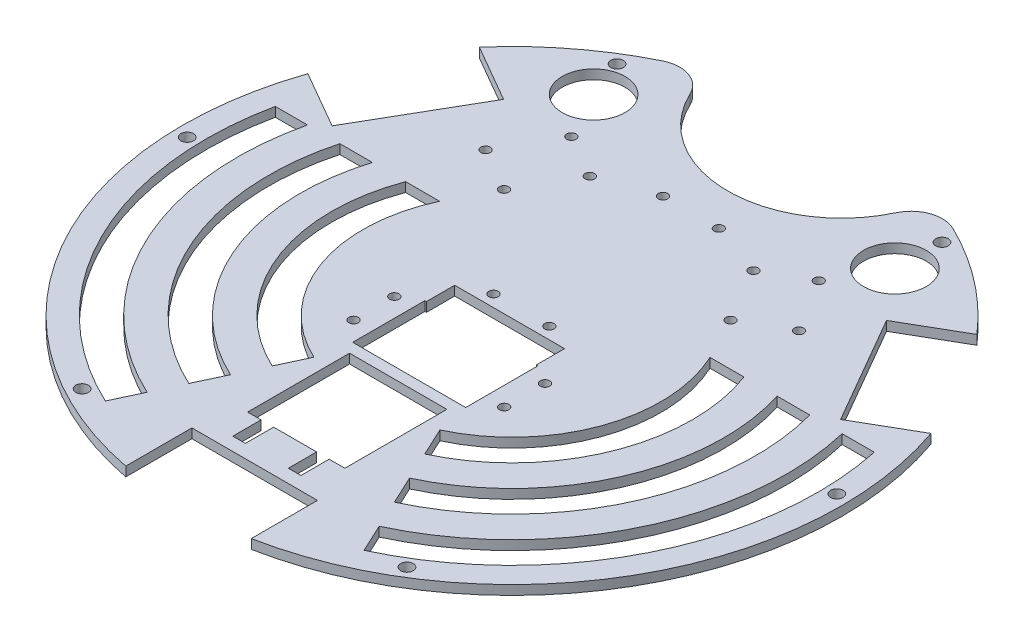
SolidWorks part; units mm, degrees
ref_plane "Alzado" through (0, 0, 0) normal (0, 0, 1) x (1, 0, 0)
ref_plane "Planta" through (0, 0, 0) normal (0, 1, 0) x (1, 0, 0)
ref_plane "Vista lateral" through (0, 0, 0) normal (1, 0, 0) x (0, 0, -1)
sketch "Croquis1" plane through (0, 0, 0) normal (0, 1, 0) x (1, 0, 0)
  circle A0 centre (0, 0) radius 105
  dimension "D1" = 210
extrude "Saliente-Extruir1" add sketch "Croquis1" along normal blind 3
sketch "Croquis2" plane through (0, 3, 0) normal (0, 1, 0) x (1, 0, 0)
  line L0 (-35.7167, 98.7386) -> (35.7167, 98.7386) construction
  line L1 (-29.7198, 68.7386) -> (25.5389, 68.7386) construction
  arc A0 (35.7167, 98.7386) -> (-35.7167, 98.7386) centre (0, 105) cw
  circle A2 centre (0, 0) radius 105 construction
  arc A3 (-35.7167, 98.7386) -> (35.7167, 98.7386) centre (0, 0) cw
  dimension "D1" = 30
extrude "Cortar-Extruir1" cut sketch "Croquis2" against normal up to surface (3 mm away) up to face at (0, 0, 105)
fillet "Redondeo1" radius 10 2 edges at (35.7167, 1.5, -98.7386) (-35.7167, 1.5, -98.7386)
sketch "Croquis3" plane through (0, 3, 0) normal (0, 1, 0) x (1, 0, 0)
  line L0 (0, 0) -> (0, -105) construction
  line L1 (-20, -105) -> (-20, -82) construction
  line L2 (-20, -82) -> (20, -82) construction
  line L3 (20, -82) -> (20, -105) construction
  line L4 (20, -105) -> (-20, -105) construction
  line L5 (-61.0141, 58.3205) -> (-85.2628, 72.3205)
  line L6 (-20, -82) -> (20, -82)
  line L7 (-20, -82) -> (-20, -110)
  line L8 (-20, -110) -> (20, -110)
  line L9 (20, -82) -> (20, -110)
  line L10 (-61.0141, 58.3205) -> (-81.0141, 23.6795)
  line L11 (-81.0141, 23.6795) -> (-105.2628, 37.6795)
  line L12 (-85.2628, 72.3205) -> (-105.2628, 37.6795)
  line L13 (81.0141, 23.6795) -> (105.2628, 37.6795)
  line L14 (81.0141, 23.6795) -> (61.0141, 58.3205)
  line L15 (61.0141, 58.3205) -> (85.2628, 72.3205)
  line L16 (105.2628, 37.6795) -> (85.2628, 72.3205)
  arc A0 (-46.2555, 94.2626) -> (46.2555, 94.2626) centre (0, 0) ccw construction
  point P23 (0, 0)
  point P29 (0, 0)
  point P44 (0, 0)
  dimension "D5" = 3
  dimension "D7" = 110
  dimension "D1" = 20
  dimension "D2" = 40
  dimension "D3" = 23
  dimension "D4" = 105
extrude "Cortar-Extruir12" cut sketch "Croquis3" against normal through all
sketch "Croquis12" plane through (0, 3, 0) normal (0, 1, 0) x (1, 0, 0)
  line L0 (0, -110) -> (0, -89) construction
  line L1 (-19, -83.92) -> (-19, -103.2666) construction
  line L2 (-19, -83.92) -> (19, -83.92) construction
  line L3 (-19, -103.2666) -> (19, -103.2666) construction
  line L4 (-19, -49.2666) -> (-11.5, -49.2666) construction
  line L6 (19, -103.2666) -> (19, -83.92) construction
  line L7 (-19, -49.2666) -> (-19, -83.92) construction
  line L8 (-15.5, -36.2666) -> (15.5, -36.2666)
  line L9 (-15.5, -36.2666) -> (-15.5, -68.7666)
  line L10 (-15.5, -68.7666) -> (15.5, -68.7666)
  line L11 (15.5, -36.2666) -> (15.5, -68.7666)
  line L12 (0, 115.6879) -> (0, -186.0714) construction
  line L13 (-18, -32.7666) -> (18, -32.7666)
  line L14 (-18, -32.7666) -> (-18, -9.7666)
  line L15 (-18, -9.7666) -> (18, -9.7666)
  line L16 (18, -32.7666) -> (18, -9.7666)
  arc A0 (-46.2555, 94.2626) -> (-79.2679, 68.8593) centre (0, 0) ccw construction
  dimension "D6" = 15.1533
  dimension "D7" = 15.5
  dimension "D1" = 21
  dimension "D2" = 38
  dimension "D3" = 19.3467
  dimension "D4" = 7.5
  dimension "D5" = 13
  dimension "D16" = 31
  dimension "D17" = 32.5
  dimension "D19" = 3.5
  dimension "D20" = 23
  dimension "D21" = 36
  dimension "D22" = 18
extrude "Cortar-Extruir13" cut sketch "Croquis12" against normal through all
sketch "Croquis15" plane through (0, 3, 0) normal (0, 1, 0) x (1, 0, 0)
  line L0 (0, -19.7666) -> (115.5798, -19.7666) construction
  line L1 (18, -9.7666) -> (-18, -9.7666) construction
  line L2 (-17.5, -11.2666) -> (-17.5, -28.2666) construction
  line L3 (-17.5, -28.2666) -> (17, -28.2666) construction
  line L4 (17, -28.2666) -> (17, -11.2666) construction
  line L5 (-17.5, -9.7666) -> (17.5, -9.7666)
  line L6 (-17.5, -9.7666) -> (-17.5, -0.7666)
  line L7 (-17.5, -0.7666) -> (17.5, -0.7666)
  line L8 (0, -114.8665) -> (0, 108.2556) construction
  line L9 (-13.9, 0) -> (-3.9, 0) construction
  line L10 (-13.9, 0) -> (-13.9, 60) construction
  line L11 (-13.9, 60) -> (-3.9, 60) construction
  line L12 (17.5, -9.7666) -> (17.5, -0.7666)
  line L13 (-17.5, -8.2666) -> (-17.5, -31.2666) construction
  line L14 (-18, -9.7666) -> (-18, -32.7666) construction
  line L15 (-17.5, -8.2666) -> (-27.5, -8.2666) construction
  line L16 (-27.5, -8.2666) -> (-27.5, -31.2666) construction
  line L17 (-27.5, -31.2666) -> (-17.5, -31.2666) construction
  line L18 (17, -11.2666) -> (-17.5, -11.2666) construction
  circle A0 centre (-24, -13.4966) radius 1.5
  circle A1 centre (-24, -26.4966) radius 1.5
  circle A2 centre (24, -26.4966) radius 1.5
  circle A3 centre (24, -13.4966) radius 1.5
  circle A4 centre (-8.9, 57) radius 1.5
  circle A5 centre (-8.9, 3) radius 1.5
  circle A6 centre (8.9, 3) radius 1.5
  circle A7 centre (8.9, 57) radius 1.5
  dimension "D7" = 23
  dimension "D8" = 11.5
  dimension "D9" = 10
  dimension "D10" = 10
  dimension "D11" = 4.77
  dimension "D12" = 3
  dimension "D17" = 3
  dimension "D18" = 5
  dimension "D19" = 3
  dimension "D20" = 3
  dimension "D21" = 3
  dimension "D22" = 5
  dimension "D13" = 3
  dimension "D23" = 3.5
  dimension "D24" = 5.23
  dimension "D31" = 3.5
  dimension "D32" = 90
  dimension "D1" = 10
  dimension "D3" = 0
  dimension "D4" = 35
  dimension "D5" = 9
  dimension "D6" = 17.5
  dimension "D14" = 10
  dimension "D15" = 13.9
  dimension "D16" = 60
  dimension "D25" = 8.5
  dimension "D26" = 0.5
  dimension "D27" = 8.5
  dimension "D28" = 17
  dimension "D29" = 10
  dimension "D30" = 23
extrude "Cortar-Extruir17" cut sketch "Croquis15" against normal through all
sketch "Croquis16" plane through (0, 3, 0) normal (0, 1, 0) x (1, 0, 0)
  line L0 (-95.4267, 20) -> (-85.1836, 20) construction
  line L1 (-41.2053, -88.365) -> (-36.9791, -79.3019) construction
  line L2 (0, 0) -> (24.3006, -52.1127) construction
  line L3 (-15.5, -36.2666) -> (-15.5, -68.7666) construction
  line L4 (15.5, -68.7666) -> (15.5, -36.2666) construction
  line L5 (85.1836, 20) -> (95.4267, 20) construction
  line L6 (64.469, 20) -> (74.8749, 20) construction
  line L7 (28.5267, -61.1758) -> (32.7529, -70.2389) construction
  line L8 (36.9791, -79.3019) -> (41.2053, -88.365) construction
  line L9 (-32.7529, -70.2389) -> (-28.5267, -61.1758) construction
  line L10 (-24.3006, -52.1127) -> (0, 0) construction
  line L11 (-74.8749, 20) -> (-64.469, 20) construction
  line L12 (-53.9096, 20) -> (53.9096, 20) construction
  line L13 (36.9791, -79.3019) -> (41.2053, -88.365)
  line L14 (85.1836, 20) -> (95.4267, 20)
  line L15 (64.469, 20) -> (74.8749, 20)
  line L16 (28.5267, -61.1758) -> (32.7529, -70.2389)
  line L17 (24.3006, -52.1127) -> (20.0744, -43.0496)
  line L18 (43.0842, 20) -> (53.9096, 20)
  line L19 (-20.0744, -43.0496) -> (-24.3006, -52.1127)
  line L20 (-28.5267, -61.1758) -> (-32.7529, -70.2389)
  line L21 (-36.9791, -79.3019) -> (-41.2053, -88.365)
  line L22 (-95.4267, 20) -> (-85.1836, 20)
  line L23 (-74.8749, 20) -> (-64.469, 20)
  line L24 (-53.9096, 20) -> (-43.0842, 20)
  arc A0 (-95.4267, 20) -> (-41.2053, -88.365) centre (0, 0) ccw
  arc A1 (-85.1836, 20) -> (-36.9791, -79.3019) centre (0, 0) ccw
  arc A2 (-74.8749, 20) -> (-32.7529, -70.2389) centre (0, 0) ccw
  arc A3 (-64.469, 20) -> (-28.5267, -61.1758) centre (0, 0) ccw
  arc A4 (-53.9096, 20) -> (-24.3006, -52.1127) centre (0, 0) ccw
  arc A5 (-43.0842, 20) -> (-20.0744, -43.0496) centre (0, 0) ccw
  arc A6 (41.2053, -88.365) -> (95.4267, 20) centre (0, 0) ccw
  arc A7 (36.9791, -79.3019) -> (85.1836, 20) centre (0, 0) ccw
  arc A8 (32.7529, -70.2389) -> (74.8749, 20) centre (0, 0) ccw
  arc A9 (28.5267, -61.1758) -> (64.469, 20) centre (0, 0) ccw
  arc A10 (24.3006, -52.1127) -> (53.9096, 20) centre (0, 0) ccw
  arc A11 (20.0744, -43.0496) -> (43.0842, 20) centre (0, 0) ccw
  circle A12 centre (-48, 74) radius 10
  circle A13 centre (48, 74) radius 10
  arc A14 (-46.2555, 94.2626) -> (-79.2679, 68.8593) centre (0, 0) ccw construction
  arc A15 (-32.8037, 89.5468) -> (32.8037, 89.5468) centre (0, 105) ccw construction
  arc A16 (79.2679, 68.8593) -> (46.2555, 94.2626) centre (0, 0) ccw construction
  circle A17 centre (-100.9679, -2.5444) radius 2
  arc A18 (-99.2679, 34.2183) -> (-20, -103.0776) centre (0, 0) ccw construction
  circle A19 centre (-52.6875, 86.1686) radius 2
  circle A20 centre (48.2804, 88.713) radius 2
  circle A21 centre (100.9679, 2.5444) radius 2
  circle A22 centre (52.6875, -86.1686) radius 2
  circle A23 centre (-48.2804, -88.713) radius 2
  point P62 (0, 0)
  point P64 (2.2188, -1.2458)
  point P66 (1.2409, -4.3993)
  dimension "D1" = 195
  dimension "D2" = 175
  dimension "D3" = 155
  dimension "D4" = 135
  dimension "D5" = 115
  dimension "D6" = 95
  dimension "D10" = 20
  dimension "D11" = 20
  dimension "D12" = 74
  dimension "D13" = 48
  dimension "D14" = 74
  dimension "D15" = 48
  dimension "D16" = 4
  dimension "D17" = 101
  dimension "D18" = 36.7628
  dimension "D7" = 25
  dimension "D8" = 25
  dimension "D9" = 20
  dimension "D19" = 6
extrude "Cortar-Extruir18" cut sketch "Croquis16" against normal blind 10
sketch "Croquis18" plane through (0, 3, 0) normal (0, 1, 0) x (1, 0, 0)
  line L0 (0, -110) -> (0, 110) construction
  circle A0 centre (-26.0632, 50.8517) radius 1.5
  circle A1 centre (-39.9244, 58.8434) radius 1.5
  circle A2 centre (-36.0721, 33.5248) radius 1.5
  circle A3 centre (-49.9333, 41.5165) radius 1.5
  circle A5 centre (36.0721, 33.5248) radius 1.5
  circle A6 centre (49.9333, 41.5165) radius 1.5
  circle A7 centre (26.0632, 50.8517) radius 1.5
  circle A8 centre (39.2741, 58.4739) radius 1.5
  dimension "D3" = 3
  dimension "D2" = 132.99
  dimension "D4" = 20.01
  dimension "D1" = 35.74
  dimension "D5" = 35.17
  dimension "D6" = 3
  dimension "D7" = 16
  dimension "D8" = 25.61
  dimension "D9" = 3
  dimension "D10" = 3
  dimension "D11" = 20.01
  dimension "D12" = 16
  dimension "D13" = 21.74
  dimension "D14" = 141.79
extrude "Cortar-Extruir19" cut sketch "Croquis18" against normal through all
sketch "Croquis19" plane through (0, 3, 0) normal (0, 1, 0) x (1, 0, 0)
  line L1 (-7.2, -68.7666) -> (-11.2, -68.7666)
  line L2 (-7.2, -68.7666) -> (-7.2, -77.7666)
  line L3 (-7.2, -77.7666) -> (-11.2, -77.7666)
  line L4 (-11.2, -68.7666) -> (-11.2, -77.7666)
  line L5 (-15.5, -68.7666) -> (15.5, -68.7666) construction
  line L6 (6.5, -77.7666) -> (10.5, -77.7666)
  line L7 (6.5, -77.7666) -> (6.5, -68.7666)
  line L8 (6.5, -68.7666) -> (10.5, -68.7666)
  line L9 (10.5, -77.7666) -> (10.5, -68.7666)
  dimension "D1" = 12.8
  dimension "D2" = 9.5
  dimension "D3" = 4
  dimension "D4" = 9
  dimension "D5" = 4
  dimension "D6" = 9
extrude "Cortar-Extruir20" cut sketch "Croquis19" against normal through all
